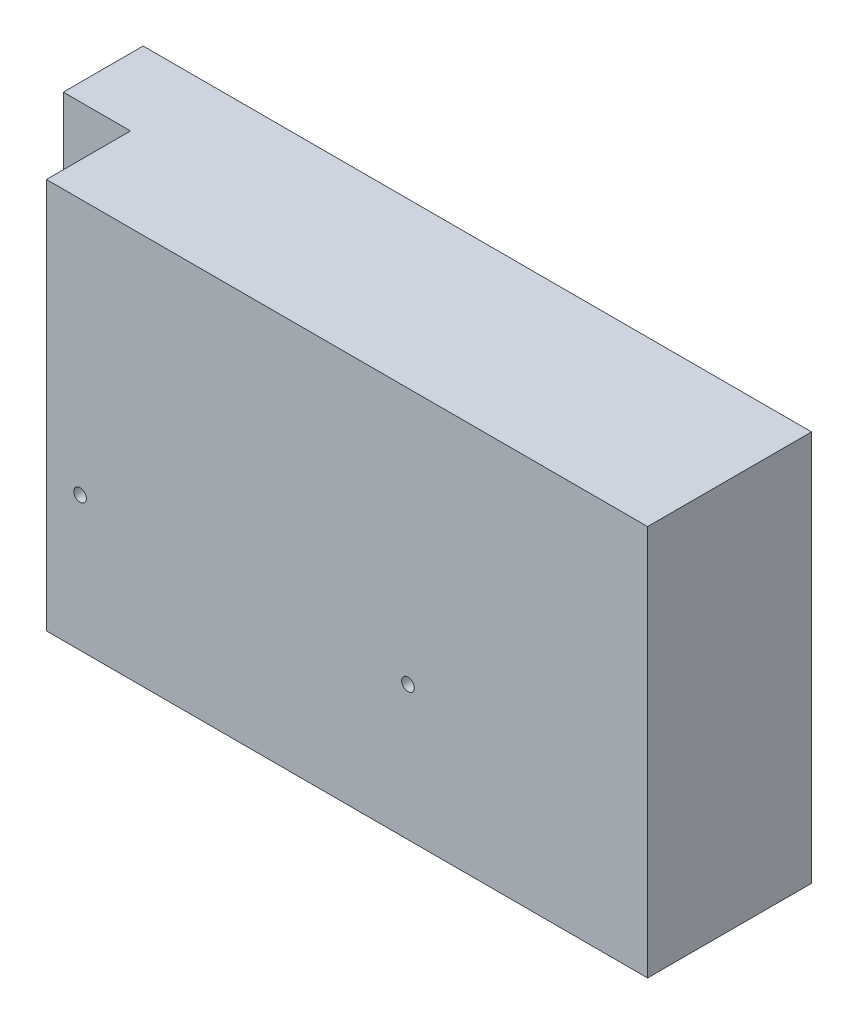
SolidWorks part; units mm, degrees
material "1023 Листовая углеродистая сталь (SS)"
ref_plane "Спереди" through (0, 0, 0) normal (0, 0, 1) x (1, 0, 0)
ref_plane "Сверху" through (0, 0, 0) normal (0, 1, 0) x (1, 0, 0)
ref_plane "Справа" through (0, 0, 0) normal (1, 0, 0) x (0, 0, -1)
sketch "Эскиз1" plane through (0, 0, 0) normal (0, 0, 1) x (1, 0, 0)
  line L1 (-79.5, 46.5) -> (79.5, 46.5)
  line L2 (-79.5, 46.5) -> (-79.5, -46.5)
  line L3 (-79.5, -46.5) -> (79.5, -46.5)
  line L4 (79.5, 46.5) -> (79.5, -46.5)
  line L5 (-79.5, 46.5) -> (79.5, -46.5) construction
  line L6 (-79.5, -46.5) -> (79.5, 46.5) construction
  point P0 (0, 0)
  dimension "D1" = 159
  dimension "D2" = 93
extrude "Бобышка-Вытянуть1" add sketch "Эскиз1" along normal blind 39
sketch "Эскиз2" plane through (0, 0, 0) normal (0, 0, -1) x (-1, 0, 0)
  line L0 (-22.5, 58.4245) -> (-22.5, -57.9342) construction
  line L1 (55.5, 58.4245) -> (55.5, -57.9342) construction
  line L2 (-104.1019, -14.5) -> (96.2629, -14.5) construction
  line L3 (-79.5, -46.5) -> (-79.5, 46.5) construction
  line L5 (79.5, -46.5) -> (-79.5, -46.5) construction
  circle A0 centre (-22.5, -14.5) radius 1.5
  circle A1 centre (55.5, -14.5) radius 1.5
  dimension "D4" = 3
  dimension "D5" = 3
  dimension "D1" = 57
  dimension "D2" = 135
  dimension "D3" = 32
extrude "Вырез-Вытянуть1" cut sketch "Эскиз2" against normal blind 39
sketch "Эскиз3" plane through (0, 0, 39) normal (0, 0, 1) x (1, 0, 0)
  line L0 (-79.5, -46.5) -> (79.5, -46.5) construction
  line L1 (-79.5, 46.5) -> (-63.5, 46.5)
  line L2 (-79.5, 46.5) -> (-79.5, -46.5)
  line L3 (-79.5, -46.5) -> (-63.5, -46.5)
  line L4 (-63.5, 46.5) -> (-63.5, -46.5)
  dimension "D1" = 16
extrude "Вырез-Вытянуть2" cut sketch "Эскиз3" against normal blind 20
